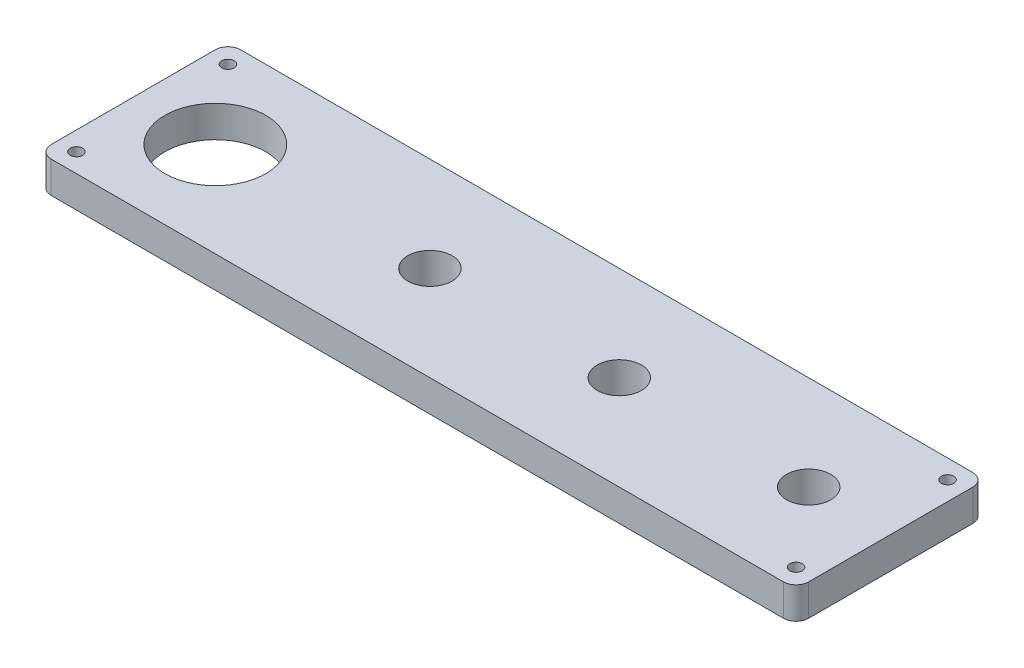
SolidWorks part; units mm, degrees
ref_plane "Front Plane" through (0, 0, 0) normal (0, 0, 1) x (1, 0, 0)
ref_plane "Top Plane" through (0, 0, 0) normal (0, 1, 0) x (1, 0, 0)
ref_plane "Right Plane" through (0, 0, 0) normal (1, 0, 0) x (0, 0, -1)
ref_plane "Plane1" through (0, 0, 0) normal (0, -1, 0) x (1, 0, 0)
sketch "Sketch1" plane through (0, 0, 0) normal (0, -1, 0) x (1, 0, 0)
  line L0 (-35.56, -19.05) -> (111.76, -19.05)
  line L1 (114.3, -16.51) -> (114.3, 16.51)
  line L2 (111.76, 19.05) -> (-35.56, 19.05)
  line L3 (-38.1, 16.51) -> (-38.1, -16.51)
  line L4 (0, 0) -> (0, 12.2265) construction
  circle A0 centre (59.69, 0) radius 4.445
  circle A1 centre (97.79, 0) radius 4.445
  circle A10 centre (21.59, 0) radius 4.445
  arc A13 (111.76, -19.05) -> (114.3, -16.51) centre (111.76, -16.51) ccw
  arc A14 (114.3, 16.51) -> (111.76, 19.05) centre (111.76, 16.51) ccw
  arc A15 (-35.56, 19.05) -> (-38.1, 16.51) centre (-35.56, 16.51) ccw
  arc A16 (-38.1, -16.51) -> (-35.56, -19.05) centre (-35.56, -16.51) ccw
  circle A17 centre (-21.59, 0) radius 10.16
  dimension "D1" = 20.32
  dimension "D5" = 2.54
  dimension "D8" = 8.89
  dimension "D9" = 38.1
  dimension "D2" = 43.18
  dimension "D3" = 152.4
  dimension "D4" = 38.1
  dimension "D6" = 19.05
  dimension "D7" = 38.1
  dimension "D10" = 38.1
extrude "Boss-Extrude1" add sketch "Sketch1" against normal blind 6.35
ref_plane "Plane2" through (0, 0, 0) normal (0, 0, 1) x (1, 0, 0)
hole_wizard "CSK for M3 Flat Head Machine Screw1" positions "Sketch3" profile "Sketch4" countersink size "M3" standard "ANSI Metric"
sketch "Sketch3" plane through (0, 9.525, 0) normal (0, 1, 0) x (1, 0, 0)
  line L4 (-35.56, 19.05) -> (111.76, 19.05) construction
  line L5 (-38.1, -16.51) -> (-38.1, 16.51) construction
  line L6 (-38.1, -16.51) -> (-38.1, 16.51) construction
  line L7 (111.76, -19.05) -> (-35.56, -19.05) construction
  line L8 (114.3, 16.51) -> (114.3, -16.51) construction
  line L9 (-35.56, 19.05) -> (111.76, 19.05) construction
  point P0 (-34.29, 15.24)
  point P2 (-34.29, -15.24)
  point P4 (110.49, -15.24)
  point P6 (110.49, 15.24)
  dimension "D1" = 3.81
  dimension "D2" = 3.81
  dimension "D3" = 3.81
  dimension "D4" = 3.81
  dimension "D5" = 3.81
  dimension "D6" = 3.81
  dimension "D7" = 3.81
  dimension "D8" = 3.81
sketch "Sketch4" plane through (-34.29, 9.525, -15.24) normal (1, 0, 0) x (0, 0, 1)
  line L0 (0, 0) -> (0, 11.0214)
  line L1 (0, 11.0214) -> (1.7, 10)
  line L2 (1.7, 10) -> (1.7, 1.45)
  line L3 (1.7, 1.45) -> (3.15, 0)
  line L5 (3.15, 0) -> (0, 0)
  line L6 (-1.7, 1.45) -> (-3.15, 0) construction
  line L10 (0, 11.0214) -> (-1.7, 10) construction
  line L11 (0, -6.35) -> (0, 107.95) construction
  dimension "Hole Dia." = 3.4
  dimension "Hole Depth" = 10
  dimension "Near C'Sink Dia." = 6.3
  dimension "Near C'Sink Angle" = 90
  dimension "Drill Angle" = 118
hole_wizard "M3x0.5 Tapped Hole1" positions "Sketch6" profile "Sketch7" tap size "M3x0.5" standard "ANSI Metric" end condition through all
sketch "Sketch6" plane through (0, 6.35, 0) normal (0, 1, 0) x (1, 0, 0)
  line L1 (-35.56, 19.05) -> (111.76, 19.05) construction
  line L2 (114.3, 16.51) -> (114.3, -16.51) construction
  point P0 (-34.29, 15.24)
  point P3 (110.49, 15.24)
  point P6 (110.49, -15.24)
  point P8 (-34.29, -15.24)
  point P15 (0, 0)
  point P16 (0, 0)
  point P17 (109.685, 15.24)
  point P18 (109.685, -15.24)
  point P25 (0, 0)
  point P26 (0, 0)
  point P27 (110.49, -28.3508)
  point P28 (110.49, -15.24)
  dimension "D1" = 3.81
  dimension "D2" = 3.81
sketch "Sketch7" plane through (-34.29, 6.35, -15.24) normal (1, 0, 0) x (0, 0, 1)
  line L0 (0, 0) -> (0, 6.35)
  line L1 (0, 6.35) -> (1.25, 6.35)
  line L2 (1.25, 6.35) -> (1.25, 0)
  line L5 (1.25, 0) -> (0, 0)
  line L11 (0, -6.35) -> (0, 107.95) construction
  dimension "Thread Major Dia." = 2.5
  dimension "Thru Tap Drill Depth" = 6.35
